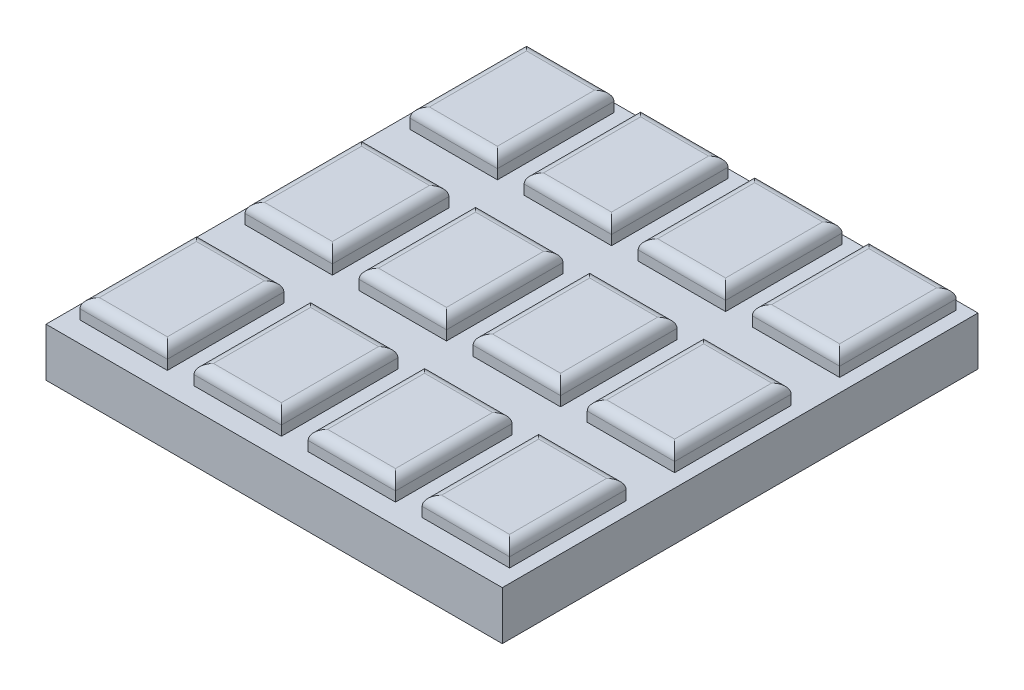
SolidWorks part; units mm, degrees
material "NEOPRENE"
ref_plane "Front Plane" through (0, 0, 0) normal (0, 0, 1) x (1, 0, 0)
ref_plane "Top Plane" through (0, 0, 0) normal (0, 1, 0) x (1, 0, 0)
ref_plane "Right Plane" through (0, 0, 0) normal (1, 0, 0) x (0, 0, -1)
sketch "Sketch1" plane through (0, 0, 0) normal (0, 1, 0) x (1, 0, 0)
  line L1 (-23.5, 24.5) -> (23.5, 24.5)
  line L2 (-23.5, 24.5) -> (-23.5, -24.5)
  line L3 (-23.5, -24.5) -> (23.5, -24.5)
  line L4 (23.5, 24.5) -> (23.5, -24.5)
  line L5 (-23.5, 24.5) -> (23.5, -24.5) construction
  line L6 (-23.5, -24.5) -> (23.5, 24.5) construction
  point P0 (0, 0)
  dimension "D1" = 47
  dimension "D2" = 49
extrude "Boss-Extrude1" add sketch "Sketch1" along normal blind 5
sketch "Sketch2" plane through (0, 5, 0) normal (0, 1, 0) x (1, 0, 0)
  line L0 (-11.75, 23.5) -> (-23.5, 11.75)
  line L1 (-23.5, 23.5) -> (23.5, 23.5)
  line L2 (-23.5, 23.5) -> (-23.5, -23.5)
  line L3 (-23.5, -23.5) -> (23.5, -23.5)
  line L4 (23.5, 23.5) -> (23.5, -23.5)
  line L5 (-23.5, 23.5) -> (23.5, -23.5) construction
  line L6 (-23.5, -23.5) -> (23.5, 23.5) construction
  line L7 (-23.5, 23.5) -> (-11.75, 23.5)
  line L8 (-23.5, 23.5) -> (-23.5, 11.75)
  line L9 (-23.5, 11.75) -> (-11.75, 11.75)
  line L10 (-11.75, 23.5) -> (-11.75, 11.75)
  line L12 (-22.125, 23.625) -> (-13.125, 23.625)
  line L13 (-22.125, 23.625) -> (-22.125, 11.625)
  line L14 (-22.125, 11.625) -> (-13.125, 11.625)
  line L15 (-13.125, 23.625) -> (-13.125, 11.625)
  line L16 (-22.125, 23.625) -> (-13.125, 11.625) construction
  line L17 (-22.125, 11.625) -> (-13.125, 23.625) construction
  point P1 (0, 0)
  point P9 (-17.625, 17.625)
  dimension "D1" = 47
  dimension "D2" = 47
  dimension "D3" = 11.75
  dimension "D4" = 11.75
  dimension "D5" = 9
  dimension "D6" = 12
extrude "Boss-Extrude2" add sketch "Sketch2" along normal blind 2 contours L13 L12 L15 L14
fillet "Fillet1" radius 1 4 edges at (-13.125, 7, -17.625) (-17.625, 7, -23.625) (-22.125, 7, -17.625) (-17.625, 7, -11.625)
pattern_linear "LPattern1" count 4 spacing 11.75 along (1, 0, 0) count 3 spacing 17 along (0, 0, 1) of "Fillet1", "Boss-Extrude2"
